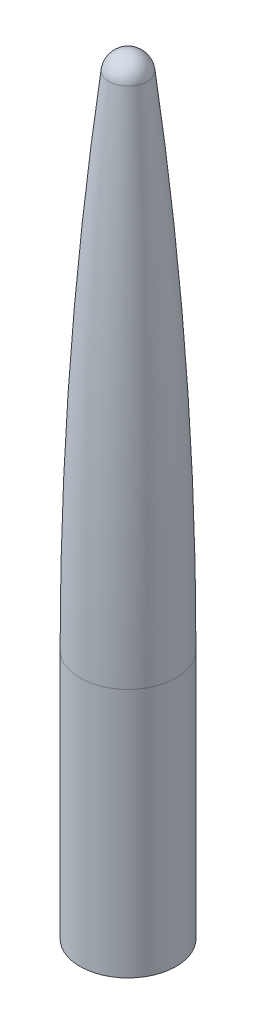
SolidWorks part; units mm, degrees
ref_plane "Front Plane" through (0, 0, 0) normal (0, 0, 1) x (1, 0, 0)
ref_plane "Top Plane" through (0, 0, 0) normal (0, 1, 0) x (1, 0, 0)
ref_plane "Right Plane" through (0, 0, 0) normal (1, 0, 0) x (0, 0, -1)
sketch "Sketch2" plane through (0, 0, 0) normal (0, 0, 1) x (1, 0, 0)
  line L0 (0, 0) -> (2.5, 0)
  line L1 (2.5, 0) -> (2.5, 13)
  line L2 (0, 0) -> (0, 40)
  arc A1 (2.5, 13) -> (0.9934, 39.115) centre (-224.5833, 13) ccw
  arc A2 (0.9934, 39.115) -> (0, 40) centre (0, 39) ccw
  point P7 (0, 18.0428)
  point P9 (2.5, 5.1562)
  point P10 (0, 0)
  point P11 (0, 0)
  point P12 (6.0716, 0)
  point P13 (9.5058, 5.386)
  point P14 (2.5, 3.0918)
  dimension "D3" = 1
  dimension "D1" = 2.5
  dimension "D2" = 40
  dimension "D4" = 13
revolve "Revolve1" add sketch "Sketch2" angle 360 about L2
